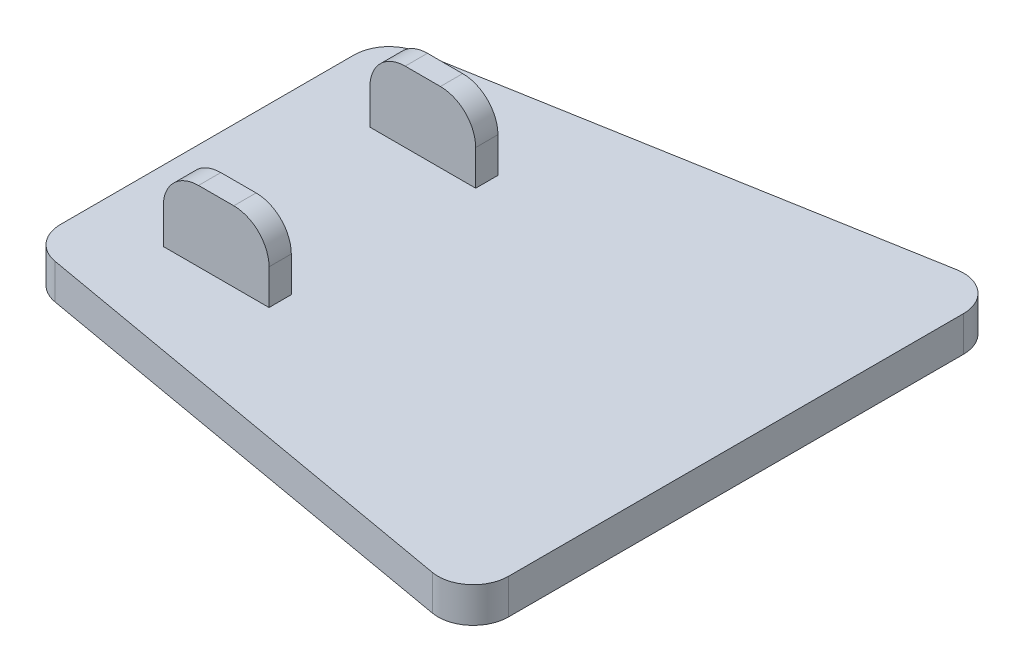
SolidWorks part; units mm, degrees
ref_plane "Front Plane" through (0, 0, 0) normal (0, 0, 1) x (1, 0, 0)
ref_plane "Top Plane" through (0, 0, 0) normal (0, 1, 0) x (1, 0, 0)
ref_plane "Right Plane" through (0, 0, 0) normal (1, 0, 0) x (0, 0, -1)
sketch "Sketch1" plane through (0, 0, 0) normal (0, 1, 0) x (1, 0, 0)
  line L0 (0, 0) -> (0, 50)
  line L1 (0, 50) -> (150, 76.449)
  line L2 (150, 76.449) -> (150, -76.449)
  line L3 (150, -76.449) -> (0, -50)
  line L4 (0, -50) -> (0, 0)
  point P3 (137.8417, -63.4578)
  dimension "D1" = 100
  dimension "D2" = 100
  dimension "D3" = 50
  dimension "D4" = 150
  dimension "D5" = 150
extrude "Boss-Extrude1" add sketch "Sketch1" along normal blind 10 contours L4 L0 L1 L2 L3
sketch "Sketch2" plane through (0, 10, 0) normal (0, 1, 0) x (1, 0, 0)
  line L1 (20, 32.4728) -> (50, 32.4728)
  line L2 (20, 32.4728) -> (20, 26.1539)
  line L3 (20, 26.1539) -> (50, 26.1539)
  line L4 (50, 32.4728) -> (50, 26.1539)
  line L5 (0, -50) -> (0, 50) construction
  line L7 (35, 32.4728) -> (35, 26.1539) construction
  point P6 (20, 29.3133)
  dimension "D1" = 20
  dimension "D2" = 30
  dimension "D3" = 15
extrude "Boss-Extrude2" add sketch "Sketch2" along normal blind 20
fillet "Fillet2" radius 10 2 edges at (50, 30, -29.3133) (20, 30, -29.3133)
mirror "Mirror1" about plane through (0, 0, 0) normal (0, 0, 1) of bodies 102
fillet "Fillet3" radius 10 4 edges at (150, 5, -76.449) (150, 5, 76.449) (0, 5, 50) (0, 5, -50)
